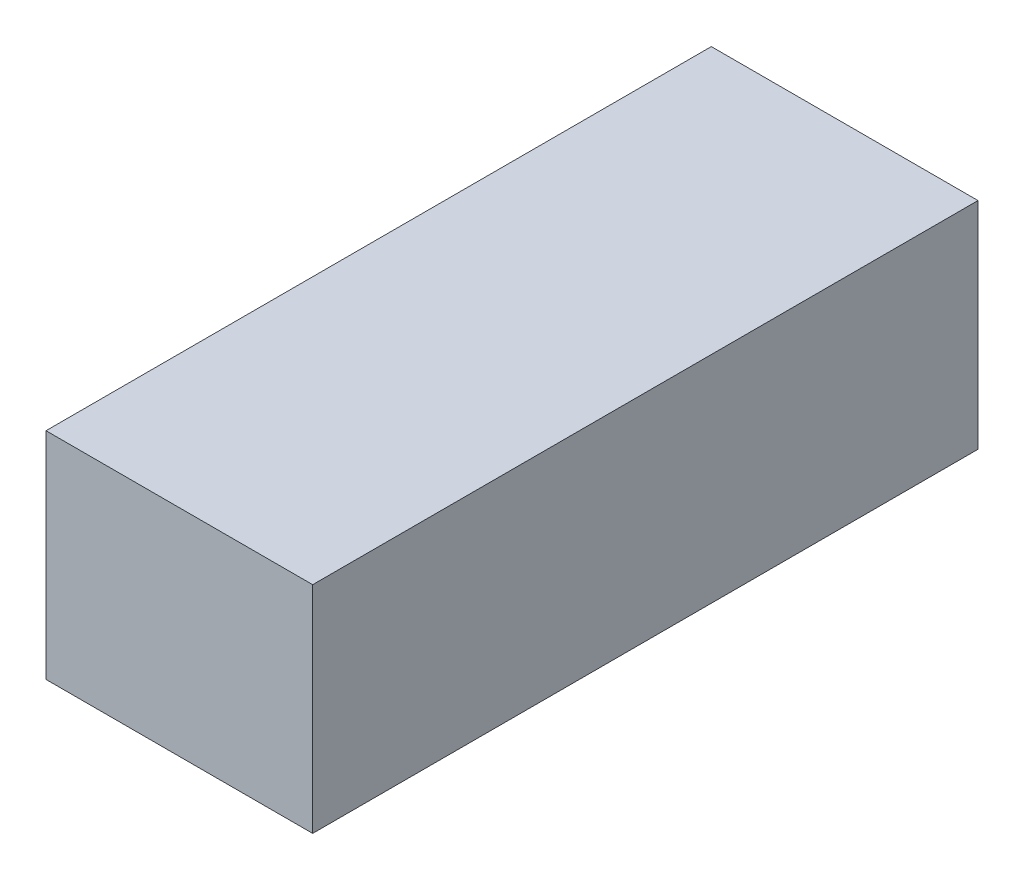
SolidWorks part; units mm, degrees
ref_plane "Front Plane" through (0, 0, 0) normal (0, 0, 1) x (1, 0, 0)
ref_plane "Top Plane" through (0, 0, 0) normal (0, 1, 0) x (1, 0, 0)
ref_plane "Right Plane" through (0, 0, 0) normal (1, 0, 0) x (0, 0, -1)
sketch "Sketch1" plane through (0, 0, 0) normal (0, 1, 0) x (1, 0, 0)
  line L1 (-13.79, 34.405) -> (13.79, 34.405)
  line L2 (-13.79, 34.405) -> (-13.79, -34.405)
  line L3 (-13.79, -34.405) -> (13.79, -34.405)
  line L4 (13.79, 34.405) -> (13.79, -34.405)
  line L5 (-13.79, 34.405) -> (13.79, -34.405) construction
  line L6 (-13.79, -34.405) -> (13.79, 34.405) construction
  point P0 (0, 0)
  dimension "D1" = 68.81
  dimension "D2" = 27.58
extrude "Boss-Extrude1" add sketch "Sketch1" along normal blind 22.28
